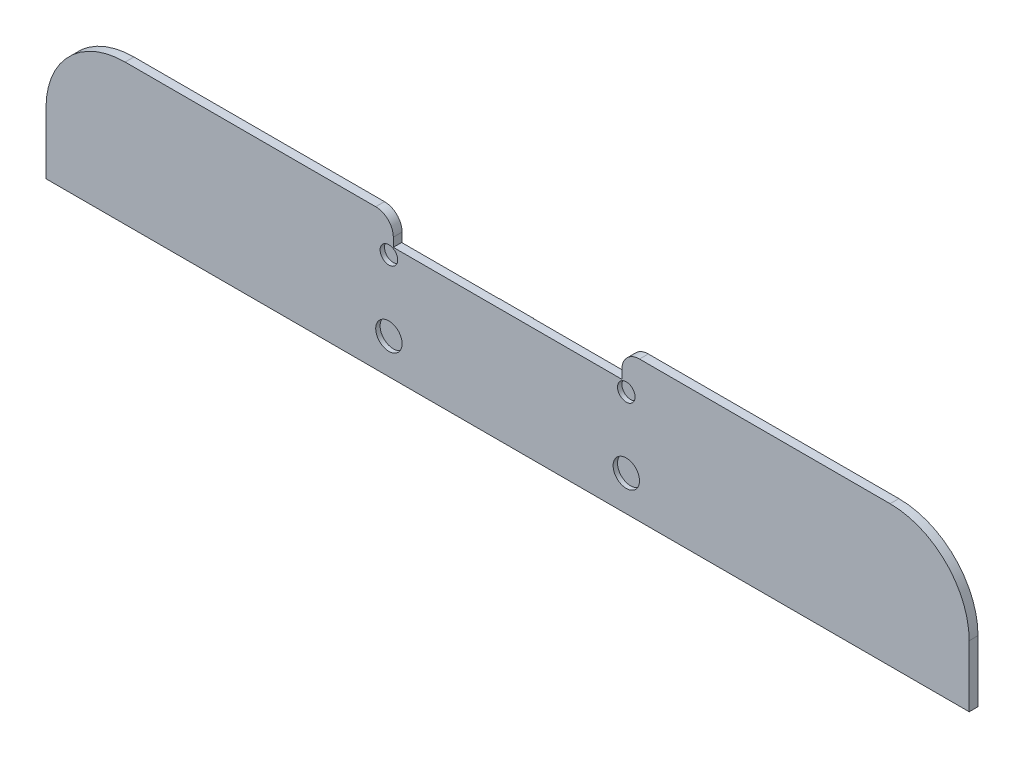
SolidWorks part; units mm, degrees
ref_plane "Front Plane" through (0, 0, 0) normal (0, 0, 1) x (1, 0, 0)
ref_plane "Top Plane" through (0, 0, 0) normal (0, 1, 0) x (1, 0, 0)
ref_plane "Right Plane" through (0, 0, 0) normal (1, 0, 0) x (0, 0, -1)
sketch "Sketch1" plane through (0, 0, 0) normal (0, 0, 1) x (1, 0, 0)
  line L1 (-525, -80) -> (525, -80)
  line L2 (-525, -80) -> (-525, 80)
  line L3 (-525, 80) -> (525, 80)
  line L4 (525, -80) -> (525, 80)
  line L5 (-525, -80) -> (525, 80) construction
  line L6 (-525, 80) -> (525, -80) construction
  point P0 (0, 0)
  dimension "D1" = 1050
  dimension "D2" = 160
extrude "Boss-Extrude1" add sketch "Sketch1" along normal blind 10 contours L1 L4 L3 L2
sketch "Sketch2" plane through (0, 0, 10) normal (0, 0, 1) x (1, 0, 0)
  line L0 (0, 0) -> (0, -101.8808) construction
  line L1 (0, 0) -> (-81.7993, 0) construction
  circle A0 centre (135, -40) radius 15
  circle A1 centre (-135, -40) radius 15
  circle A2 centre (-135, 40) radius 10
  circle A3 centre (135, 40) radius 10
  dimension "D1" = 30
  dimension "D2" = 30
  dimension "D3" = 20
  dimension "D4" = 20
  dimension "D5" = 80
  dimension "D6" = 270
extrude "Cut-Extrude3" cut sketch "Sketch2" against normal blind 5 contours A2 | A3 | A0 | A1
fillet "Fillet1" radius 90 1 edges at (525, 80, 5)
fillet "Fillet2" radius 90 1 edges at (-525, 80, 5)
sketch "Sketch3" plane through (0, 0, 0) normal (0, 0, -1) x (-1, 0, 0)
  line L0 (435, 80) -> (-435, 80) construction
  line L3 (130, -80) -> (-130, -80)
  line L4 (130, -80) -> (130, 80)
  line L5 (130, 80) -> (-130, 80)
  line L6 (-130, -80) -> (-130, 80)
  line L7 (130, -80) -> (-130, 80) construction
  line L8 (130, 80) -> (-130, -80) construction
  point P0 (0, 0)
  dimension "D1" = 130
extrude "Cut-Extrude4" cut sketch "Sketch3" against normal blind 0.5 contours L6 L5 L4 L3
sketch "Sketch4" plane through (0, 0, 0.5) normal (0, 0, -1) x (-1, 0, 0)
  line L0 (130, 80) -> (-130, 80) construction
  line L1 (20, -80) -> (-20, -80)
  line L2 (20, -80) -> (20, 80)
  line L3 (20, 80) -> (-20, 80)
  line L4 (-20, -80) -> (-20, 80)
  line L5 (20, -80) -> (-20, 80) construction
  line L6 (20, 80) -> (-20, -80) construction
  point P0 (0, 0)
  dimension "D1" = 20
extrude "Boss-Extrude2" add sketch "Sketch4" along normal blind 0.25
sketch "Sketch5" plane through (0, 80, 0) normal (0, 1, 0) x (1, 0, 0)
  line L0 (-130, -0.5) -> (-130, -10)
  line L1 (-435, -10) -> (435, -10) construction
  line L2 (-130, -10) -> (130, -10)
  line L3 (130, -10) -> (130, -0.5)
  line L4 (-130, -0.5) -> (130, -0.5)
extrude "Cut-Extrude5" cut sketch "Sketch5" against normal blind 30
sketch "Sketch6" plane through (0, 0, 0.25) normal (0, 0, -1) x (-1, 0, 0)
  line L1 (20, 50) -> (-20, 50)
  line L2 (20, 50) -> (20, 80)
  line L3 (20, 80) -> (-20, 80)
  line L4 (-20, 50) -> (-20, 80)
extrude "Cut-Extrude7" cut sketch "Sketch6" against normal blind 30
fillet "Fillet3" radius 20 1 edges at (130, 80, 5)
fillet "Fillet4" radius 20 1 edges at (-130, 80, 5)
